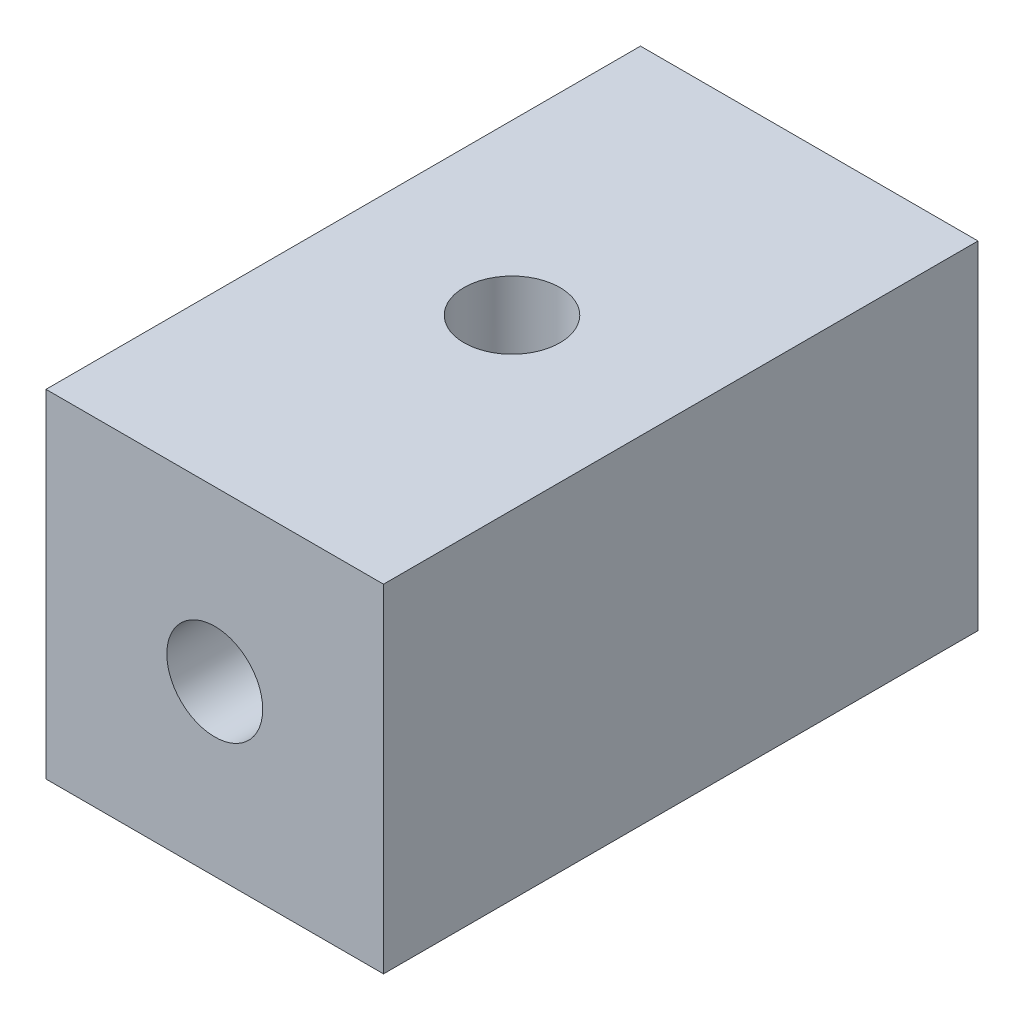
SolidWorks part; units mm, degrees
ref_plane "Front Plane" through (0, 0, 0) normal (0, 0, 1) x (1, 0, 0)
ref_plane "Top Plane" through (0, 0, 0) normal (0, 1, 0) x (1, 0, 0)
ref_plane "Right Plane" through (0, 0, 0) normal (1, 0, 0) x (0, 0, -1)
sketch "Sketch1" plane through (0, 0, 0) normal (0, 0, 1) x (1, 0, 0)
  line L1 (-11.176, 11.176) -> (11.176, 11.176)
  line L2 (-11.176, 11.176) -> (-11.176, -11.176)
  line L3 (-11.176, -11.176) -> (11.176, -11.176)
  line L4 (11.176, 11.176) -> (11.176, -11.176)
  line L5 (-11.176, 11.176) -> (11.176, -11.176) construction
  line L6 (-11.176, -11.176) -> (11.176, 11.176) construction
  circle A0 centre (0, 0) radius 3.175
  point P0 (0, 0)
  dimension "D3" = 6.35
  dimension "D1" = 22.352
  dimension "D2" = 22.352
extrude "Boss-Extrude1" add sketch "Sketch1" along normal blind 39.37
sketch "Sketch2" plane through (0, 11.176, 0) normal (0, 1, 0) x (1, 0, 0)
  line L0 (11.176, 0) -> (-11.176, 0) construction
  line L1 (-11.176, -39.37) -> (-11.176, 0) construction
  circle A0 centre (0, -19.685) radius 3.175
  dimension "D1" = 19.685
  dimension "D2" = 11.176
  dimension "D3" = 6.35
extrude "Cut-Extrude1" cut sketch "Sketch2" against normal blind 25.4
